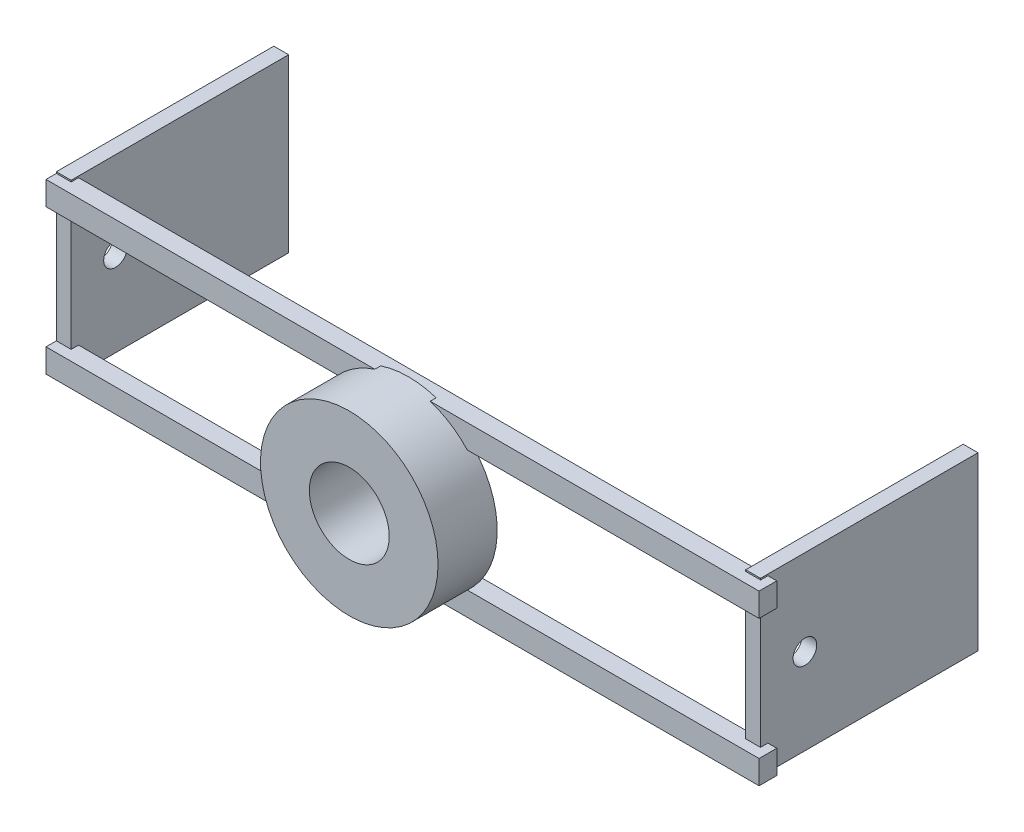
SolidWorks part; units mm, degrees
ref_plane "Front Plane" through (0, 0, 0) normal (0, 0, 1) x (1, 0, 0)
ref_plane "Top Plane" through (0, 0, 0) normal (0, 1, 0) x (1, 0, 0)
ref_plane "Right Plane" through (0, 0, 0) normal (1, 0, 0) x (0, 0, -1)
ref_plane "Plane1" through (0, 0, 190) normal (0, 0, 1) x (1, 0, 0)
sketch "Sketch1" plane through (0, 0, 190) normal (0, 0, 1) x (1, 0, 0)
  circle A0 centre (300, 300) radius 60
extrude "Boss-Extrude1" add sketch "Sketch1" along normal blind 40
ref_plane "Plane2" through (0, 0, 182) normal (0, 0, 1) x (1, 0, 0)
sketch "Sketch2" plane through (0, 0, 182) normal (0, 0, 1) x (1, 0, 0)
  line L1 (59, 341) -> (541, 341)
  line L2 (59, 341) -> (59, 357)
  line L3 (59, 357) -> (541, 357)
  line L4 (541, 341) -> (541, 357)
extrude "Boss-Extrude2" add sketch "Sketch2" along normal blind 12
ref_plane "Plane3" through (0, 0, 182) normal (0, 0, 1) x (1, 0, 0)
sketch "Sketch3" plane through (0, 0, 182) normal (0, 0, 1) x (1, 0, 0)
  line L1 (59, 243) -> (541, 243)
  line L2 (59, 243) -> (59, 259)
  line L3 (59, 259) -> (541, 259)
  line L4 (541, 243) -> (541, 259)
extrude "Boss-Extrude3" add sketch "Sketch3" along normal blind 12
ref_plane "Plane4" through (525, 0, 0) normal (1, 0, 0) x (0, 0, -1)
sketch "Sketch4" plane through (525, 0, 0) normal (1, 0, 0) x (0, 0, -1)
  line L1 (-40, 242) -> (-187, 242)
  line L2 (-40, 242) -> (-40, 358)
  line L3 (-40, 358) -> (-187, 358)
  line L4 (-187, 242) -> (-187, 358)
extrude "Boss-Extrude4" add sketch "Sketch4" along normal blind 10
ref_plane "Plane5" through (59, 0, 0) normal (1, 0, 0) x (0, 0, -1)
sketch "Sketch5" plane through (59, 0, 0) normal (1, 0, 0) x (0, 0, -1)
  line L1 (-40, 242) -> (-187, 242)
  line L2 (-40, 242) -> (-40, 358)
  line L3 (-40, 358) -> (-187, 358)
  line L4 (-187, 242) -> (-187, 358)
extrude "Boss-Extrude5" add sketch "Sketch5" along normal blind 10
sketch "Sketch6" plane through (0, 0, 230) normal (0, 0, 1) x (1, 0, 0)
  circle A0 centre (300, 300) radius 27
extrude "Cut-Extrude1" cut sketch "Sketch6" against normal blind 210
sketch "Sketch7" plane through (535, 0, 0) normal (1, 0, 0) x (0, 0, -1)
  circle A0 centre (-157, 300) radius 8
extrude "Cut-Extrude2" cut sketch "Sketch7" against normal blind 502
